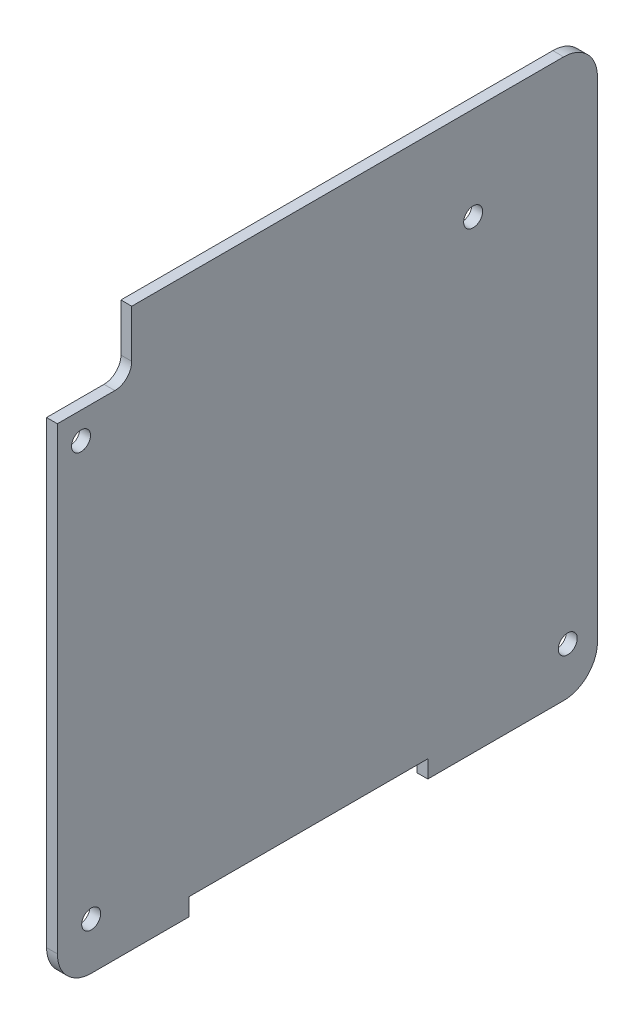
SolidWorks part; units mm, degrees
ref_plane "Front Plane" through (0, 0, 0) normal (0, 0, 1) x (1, 0, 0)
ref_plane "Top Plane" through (0, 0, 0) normal (0, 1, 0) x (1, 0, 0)
ref_plane "Right Plane" through (0, 0, 0) normal (1, 0, 0) x (0, 0, -1)
sketch "Sketch1" plane through (0, 0, 0) normal (1, 0, 0) x (0, 0, -1)
  line L0 (-35.2974, -41.6882) -> (-20.8094, -41.6882)
  line L1 (-40.2974, -36.6882) -> (-40.2974, 31.2284)
  line L2 (-29.2974, 40.7848) -> (34.592, 40.7848)
  line L3 (39.592, -36.6882) -> (39.592, 35.7848)
  line L4 (-40.2974, -41.6882) -> (39.592, 40.7848) construction
  line L5 (-29.6582, 31.2284) -> (39.592, -41.6882) construction
  line L6 (-40.2974, 31.2284) -> (-31.7974, 31.2284)
  line L7 (-29.2974, 40.7848) -> (-29.2974, 33.7284)
  line L8 (-20.8094, -41.6882) -> (-20.8094, -39.0971)
  line L9 (-20.8094, -39.0971) -> (14.4966, -39.0971)
  line L10 (14.4966, -39.0971) -> (14.4966, -41.6882)
  line L11 (14.4966, -41.6882) -> (34.592, -41.6882)
  circle A0 centre (-36.7974, 27.2848) radius 1.4
  circle A1 centre (21.2026, 26.9848) radius 1.4
  circle A2 centre (-35.2974, -34.7152) radius 1.4
  circle A3 centre (35.2026, -34.7152) radius 1.4
  arc A4 (-31.7974, 31.2284) -> (-29.2974, 33.7284) centre (-31.7974, 33.7284) ccw
  arc A5 (-35.2974, -41.6882) -> (-40.2974, -36.6882) centre (-35.2974, -36.6882) cw
  arc A6 (34.592, -41.6882) -> (39.592, -36.6882) centre (34.592, -36.6882) ccw
  arc A7 (34.592, 40.7848) -> (39.592, 35.7848) centre (34.592, 35.7848) cw
  point P0 (0.042, -0.0442)
  point P30 (21.1439, 24.6776)
  point P32 (0, 0)
  point P33 (0, 0)
  dimension "D7" = 2.5
  dimension "D8" = 5
  dimension "D1" = 3.5
  dimension "D2" = 58
  dimension "D3" = 14
  dimension "D4" = 61.7
  dimension "D5" = 13.5
  dimension "D6" = 1.5
  dimension "D9" = 19.488
  dimension "D10" = 2.5911
  dimension "D11" = 35.306
  dimension "D12" = 62
  dimension "D13" = 0.3
extrude "Boss-Extrude1" add sketch "Sketch1" along normal mid plane 1.6
